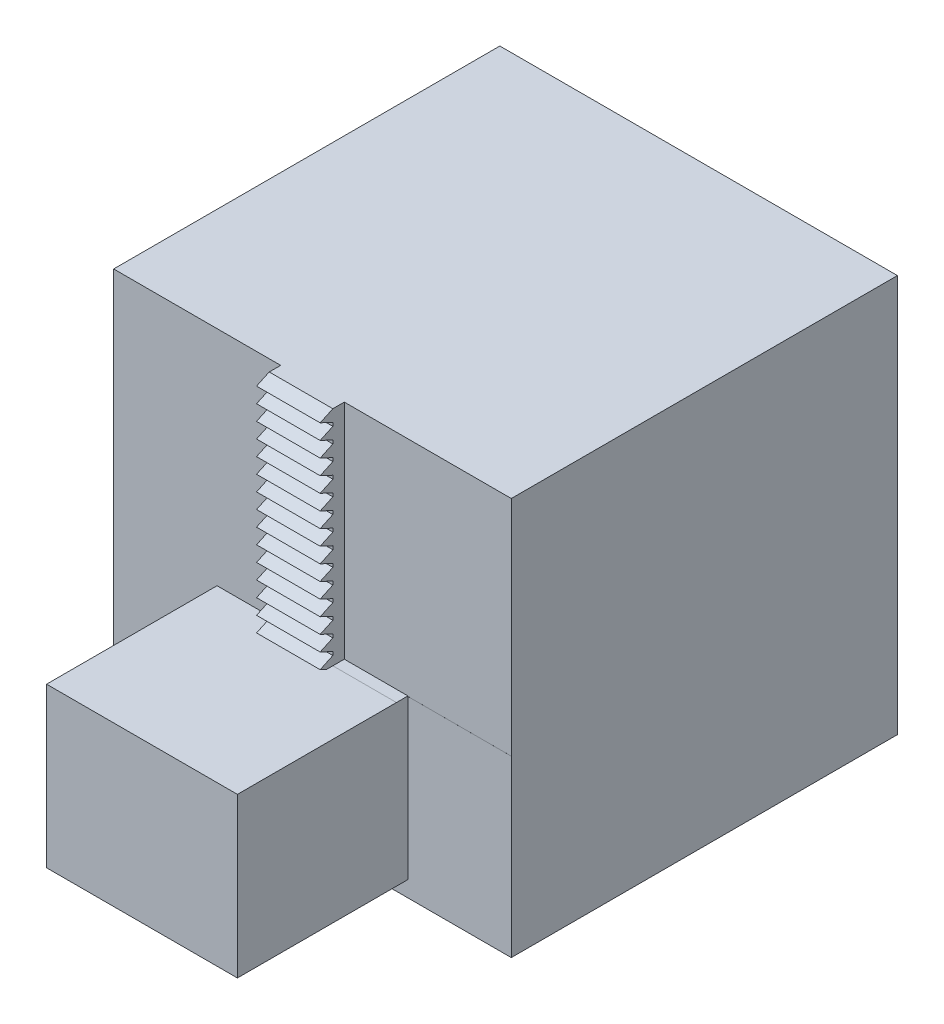
SolidWorks part; units mm, degrees
ref_plane "Front Plane" through (0, 0, 0) normal (0, 0, 1) x (1, 0, 0)
ref_plane "Top Plane" through (0, 0, 0) normal (0, 1, 0) x (1, 0, 0)
ref_plane "Right Plane" through (0, 0, 0) normal (1, 0, 0) x (0, 0, -1)
sketch "Sketch1" plane through (0, 0, 0) normal (0, 1, 0) x (1, 0, 0)
  line L1 (12.5, 12.5) -> (-12.5, 12.5)
  line L2 (12.5, 12.5) -> (12.5, -12.5)
  line L3 (12.5, -12.5) -> (-12.5, -12.5)
  line L4 (-12.5, 12.5) -> (-12.5, -12.5)
  line L5 (12.5, 12.5) -> (-12.5, -12.5) construction
  line L6 (12.5, -12.5) -> (-12.5, 12.5) construction
  point P0 (0, 0)
  dimension "D1" = 25
  dimension "D2" = 25
extrude "Boss-Extrude1" add sketch "Sketch1" along normal blind 25
sketch "Sketch2" plane through (0, 0, 12.5) normal (0, 0, 1) x (1, 0, 0)
  line L0 (0, 0) -> (0, 25) construction
  line L1 (-12.5, 0) -> (12.5, 0) construction
  line L2 (-12.5, 25) -> (12.5, 25) construction
  line L4 (6, 1) -> (-6, 1)
  line L5 (6, 1) -> (6, 11)
  line L6 (6, 11) -> (-6, 11)
  line L7 (-6, 1) -> (-6, 11)
  line L8 (6, 1) -> (-6, 11) construction
  line L9 (6, 11) -> (-6, 1) construction
  point P6 (0, 6)
  dimension "D1" = 1
  dimension "D2" = 10
  dimension "D3" = 12
extrude "Boss-Extrude2" add sketch "Sketch2" along normal blind 10
ref_plane "Plane1" through (0, 0, 0) normal (1, 0, 0) x (0, 0, -1)
sketch "Sketch3" plane through (0, 0, 0) normal (1, 0, 0) x (0, 0, -1)
  line L0 (-12.5, 25) -> (-12.5, 24.2575)
  line L1 (-12.5, 25) -> (-12.5, 0) construction
  line L3 (-13.2979, 24.6287) -> (-12.5, 24.6287) construction
  line L13 (-12.5, 25) -> (-13.2979, 24.6287)
  line L14 (-12.5, 24.2575) -> (-13.2979, 24.6287)
  dimension "D1" = 0.88
extrude "Boss-Extrude4" add sketch "Sketch3" along normal mid plane 4 contours L13 L14 L0
pattern_linear "LPattern1" count 15 spacing 0.96 along (0, -1, 0) of "Boss-Extrude4"
sketch "Sketch4" plane through (12.5, 0, 0) normal (1, 0, 0) x (0, 0, -1)
  line L1 (-12.5, 25) -> (-11.7793, 25)
  line L2 (-12.5, 25) -> (-12.5, 10.9696)
  line L3 (-12.5, 10.9696) -> (-11.7793, 10.9696)
  line L4 (-11.7793, 25) -> (-11.7793, 10.9696)
extrude "Cut-Extrude1" cut sketch "Sketch4" against normal up to surface (10.5 mm away) up to face at (2, 24.6287, 12.766)
sketch "Sketch5" plane through (0, 25, 0) normal (0, 1, 0) x (1, 0, 0)
  line L0 (-12.5, 12.5) -> (-12.5, -12.5) construction
  line L1 (-2, -12.5) -> (-12.5, -12.5)
  line L2 (-2, -12.5) -> (-2, -11.78)
  line L3 (-2, -11.78) -> (-12.5, -11.78)
  line L4 (-12.5, -12.5) -> (-12.5, -11.78)
  dimension "D1" = 0.72
extrude "Cut-Extrude2" cut sketch "Sketch5" against normal blind 14.3
sketch "Sketch7" plane through (0, 0, 12.5) normal (0, 0, 1) x (1, 0, 0)
  line L0 (-6, 10.7) -> (-12.5, 10.7)
  line L1 (-12.5, 10.7) -> (-12.5, 0)
  line L2 (-12.5, 0) -> (12.5, 0)
  line L3 (12.5, 0) -> (12.5, 10.9696)
  line L4 (12.5, 10.9696) -> (6, 10.9696)
  line L5 (6, 10.9696) -> (6, 1)
  line L6 (6, 1) -> (-6, 1)
  line L7 (-6, 1) -> (-6, 10.7)
extrude "Cut-Extrude3" cut sketch "Sketch7" against normal blind 0.72
sketch "Sketch8" plane through (-6, 0, 0) normal (-1, 0, 0) x (0, 0, 1)
  line L0 (12.5, 11) -> (12.5, 10.7) construction
  line L1 (12.5, 11) -> (11.78, 11)
  line L2 (12.5, 11) -> (12.5, 10.7)
  line L3 (12.5, 10.7) -> (11.78, 10.7)
  line L4 (11.78, 11) -> (11.78, 10.7)
  line L5 (22.5, 11) -> (12.5, 11) construction
extrude "Boss-Extrude5" add sketch "Sketch8" against normal up to next
sketch "Sketch10" plane through (2, 0, 0) normal (1, 0, 0) x (0, 0, -1)
  line L1 (-12.5, 10.9696) -> (-11.7793, 10.9696)
  line L2 (-12.5, 10.9696) -> (-12.5, 11)
  line L3 (-12.5, 11) -> (-11.7793, 11)
  line L4 (-11.7793, 10.9696) -> (-11.7793, 11)
  point P5 (0, 0)
  point P7 (0, 0)
extrude "Boss-Extrude6" add sketch "Sketch10" along normal blind 4
